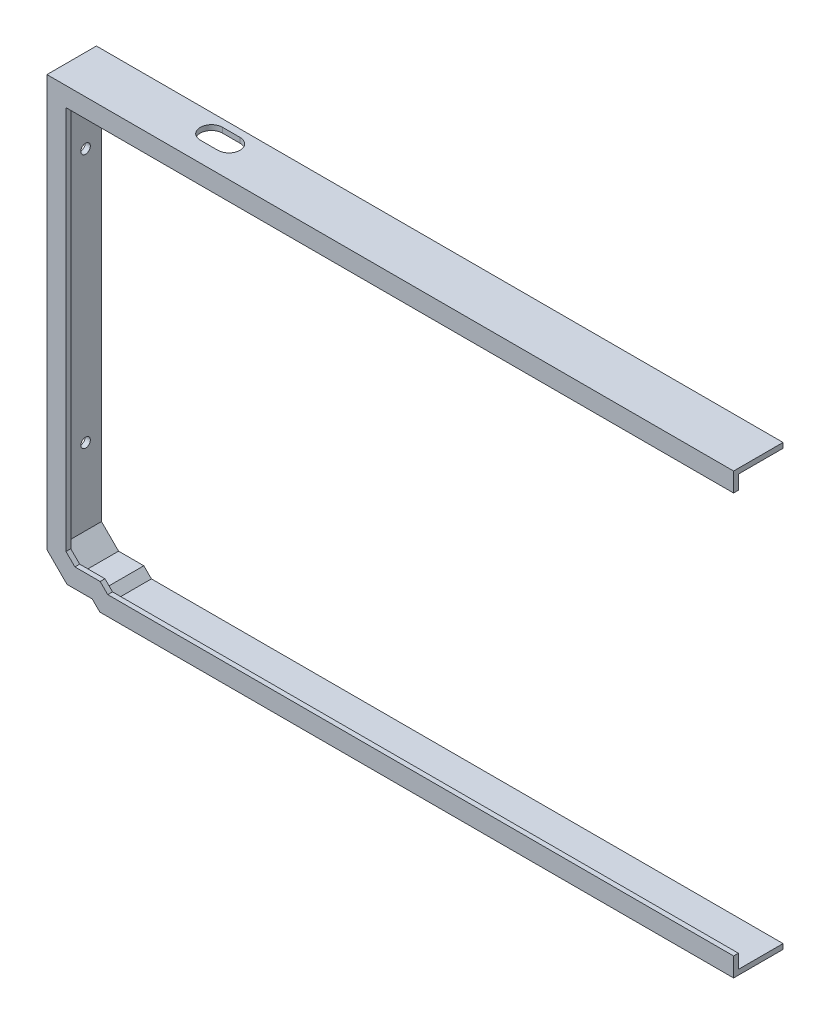
SolidWorks part; units mm, degrees
ref_plane "Přední rovina" through (0, 0, 0) normal (0, 0, 1) x (1, 0, 0)
ref_plane "Horní rovina" through (0, 0, 0) normal (0, 1, 0) x (1, 0, 0)
ref_plane "Pravá rovina" through (0, 0, 0) normal (1, 0, 0) x (0, 0, -1)
sketch "Skica1" plane through (0, 0, 0) normal (0, 0, 1) x (1, 0, 0)
  line L0 (0, 0) -> (428.28, 0) construction
  line L1 (0, 0) -> (0, -126.92) construction
  line L2 (428.28, 0) -> (428.28, -126.92) construction
  line L3 (0, -126.92) -> (5.3104, -132.2304) construction
  line L4 (428.28, -126.92) -> (422.9696, -132.2304) construction
  line L5 (5.3104, -132.2304) -> (13.2504, -132.2304) construction
  line L6 (422.9696, -132.2304) -> (415.0296, -132.2304) construction
  line L7 (13.2504, -132.2304) -> (15.6333, -134.6133) construction
  line L8 (415.0296, -132.2304) -> (412.6467, -134.6133) construction
  line L9 (412.6467, -134.6133) -> (15.6333, -134.6133) construction
  line L10 (-0.1, 0.1) -> (428.38, 0.1)
  line L11 (428.38, 0.1) -> (428.38, -126.9614)
  line L12 (428.38, -126.9614) -> (423.011, -132.3304)
  line L13 (423.011, -132.3304) -> (415.071, -132.3304)
  line L14 (415.071, -132.3304) -> (412.6881, -134.7133)
  line L15 (412.6881, -134.7133) -> (15.5919, -134.7133)
  line L16 (13.209, -132.3304) -> (15.5919, -134.7133)
  line L17 (5.269, -132.3304) -> (13.209, -132.3304)
  line L18 (-0.1, -126.9614) -> (5.269, -132.3304)
  line L19 (-0.1, 0.1) -> (-0.1, -126.9614)
  line L20 (-1.7, 1.7) -> (429.98, 1.7)
  line L21 (429.98, 1.7) -> (429.98, -127.6242)
  line L22 (429.98, -127.6242) -> (423.6738, -133.9304)
  line L23 (423.6738, -133.9304) -> (415.7338, -133.9304)
  line L24 (415.7338, -133.9304) -> (413.3508, -136.3133)
  line L25 (413.3508, -136.3133) -> (14.9292, -136.3133)
  line L26 (12.5462, -133.9304) -> (14.9292, -136.3133)
  line L27 (4.6062, -133.9304) -> (12.5462, -133.9304)
  line L28 (-1.7, -127.6242) -> (4.6062, -133.9304)
  line L29 (-1.7, 1.7) -> (-1.7, -127.6242)
  dimension "D1" = 428.28
  dimension "D2" = 126.92
  dimension "D3" = 126.92
  dimension "D4" = 7.51
  dimension "D5" = 7.51
  dimension "D6" = 135
  dimension "D7" = 135
  dimension "D8" = 7.94
  dimension "D9" = 7.94
  dimension "D10" = 3.37
  dimension "D11" = 3.37
  dimension "D12" = 135
  dimension "D13" = 0.1
  dimension "D14" = 1.6
extrude "Přidat vysunutím1" add sketch "Skica1" against normal blind 14.05
sketch "Skica2" plane through (0, 0, 0) normal (0, 0, 1) x (1, 0, 0)
  line L20 (4.3, -4.3) -> (4.3, -125.1389)
  line L21 (4.3, -125.1389) -> (7.0915, -127.9304)
  line L22 (7.0915, -127.9304) -> (15.0315, -127.9304)
  line L23 (15.0315, -127.9304) -> (17.4144, -130.3133)
  line L24 (17.4144, -130.3133) -> (410.8656, -130.3133)
  line L25 (410.8656, -130.3133) -> (413.2485, -127.9304)
  line L26 (413.2485, -127.9304) -> (421.1885, -127.9304)
  line L27 (421.1885, -127.9304) -> (423.98, -125.1389)
  line L28 (423.98, -125.1389) -> (423.98, -4.3)
  line L29 (423.98, -4.3) -> (4.3, -4.3)
  line L30 (4.3, -4.3) -> (4.3, -125.1389)
  line L31 (4.3, -125.1389) -> (7.0915, -127.9304)
  line L32 (7.0915, -127.9304) -> (15.0315, -127.9304)
  line L33 (15.0315, -127.9304) -> (17.4144, -130.3133)
  line L34 (17.4144, -130.3133) -> (410.8656, -130.3133)
  line L35 (410.8656, -130.3133) -> (413.2485, -127.9304)
  line L36 (413.2485, -127.9304) -> (421.1885, -127.9304)
  line L37 (421.1885, -127.9304) -> (423.98, -125.1389)
  line L38 (423.98, -125.1389) -> (423.98, -4.3)
  line L39 (423.98, -4.3) -> (4.3, -4.3)
  line L50 (-1.7, 1.7) -> (-1.7, -127.6242)
  line L51 (-1.7, -127.6242) -> (4.6062, -133.9304)
  line L52 (4.6062, -133.9304) -> (12.5462, -133.9304)
  line L53 (12.5462, -133.9304) -> (14.9292, -136.3133)
  line L54 (14.9292, -136.3133) -> (413.3508, -136.3133)
  line L55 (413.3508, -136.3133) -> (415.7338, -133.9304)
  line L56 (415.7338, -133.9304) -> (423.6738, -133.9304)
  line L57 (423.6738, -133.9304) -> (429.98, -127.6242)
  line L58 (429.98, -127.6242) -> (429.98, 1.7)
  line L59 (429.98, 1.7) -> (-1.7, 1.7)
  line L60 (-1.7, 1.7) -> (-1.7, -127.6242)
  line L61 (-1.7, -127.6242) -> (4.6062, -133.9304)
  line L62 (4.6062, -133.9304) -> (12.5462, -133.9304)
  line L63 (12.5462, -133.9304) -> (14.9292, -136.3133)
  line L64 (14.9292, -136.3133) -> (413.3508, -136.3133)
  line L65 (413.3508, -136.3133) -> (415.7338, -133.9304)
  line L66 (415.7338, -133.9304) -> (423.6738, -133.9304)
  line L67 (423.6738, -133.9304) -> (429.98, -127.6242)
  line L68 (429.98, -127.6242) -> (429.98, 1.7)
  line L69 (429.98, 1.7) -> (-1.7, 1.7)
  dimension "D1" = 6
  dimension "D2" = 0
extrude "Přidat vysunutím2" add sketch "Skica2" along normal blind 1.5
sketch "Skica3" plane through (0, 1.7, 0) normal (0, 1, 0) x (1, 0, 0)
  line L0 (-1.7, 8.25) -> (43.01, 8.25) construction
  line L1 (-1.7, 14.05) -> (-1.7, -1.5) construction
  line L2 (429.98, -1.5) -> (-1.7, -1.5) construction
  line L3 (45.76, 8.25) -> (40.26, 8.25) construction
  line L4 (45.76, 4.75) -> (40.26, 4.75)
  line L5 (45.76, 11.75) -> (40.26, 11.75)
  arc A0 (45.76, 4.75) -> (45.76, 11.75) centre (45.76, 8.25) ccw
  arc A1 (40.26, 11.75) -> (40.26, 4.75) centre (40.26, 8.25) ccw
  point P6 (40.26, 8.25)
  point P9 (43.01, 8.25)
  dimension "D1" = 9.75
  dimension "D2" = 44.71
  dimension "D3" = 2.75
  dimension "D4" = 7
extrude "Odebrat vysunutím1" cut sketch "Skica3" against normal up to surface (1.6 mm away) up to face at (214.14, 0.1, -7.025)
sketch "Skica4" plane through (-1.7, 0, 0) normal (-1, 0, 0) x (0, 0, 1)
  line L0 (-14.05, -62.9621) -> (1.5, -62.9621) construction
  line L1 (-14.05, 1.7) -> (-14.05, -127.6242) construction
  line L2 (1.5, 1.7) -> (1.5, -127.6242) construction
  circle A0 centre (-9.05, -22.9621) radius 1.5
  circle A1 centre (-9.05, -102.9621) radius 1.5
  dimension "D2" = 3
  dimension "D3" = 3
  dimension "D1" = 40
  dimension "D4" = 5
extrude "Odebrat vysunutím2" cut sketch "Skica4" against normal up to surface (431.68 mm away) up to face at (429.98, -62.9621, -6.275)
sketch "Skica5" plane through (0, 1.7, 0) normal (0, 1, 0) x (1, 0, 0)
  line L0 (429.98, -1.5) -> (-1.7, -1.5) construction
  line L1 (214.14, -1.5) -> (429.98, -1.5)
  line L2 (214.14, -1.5) -> (214.14, 14.05)
  line L3 (214.14, 14.05) -> (429.98, 14.05)
  line L4 (429.98, -1.5) -> (429.98, 14.05)
extrude "Odebrat vysunutím3" cut sketch "Skica5" against normal through all
